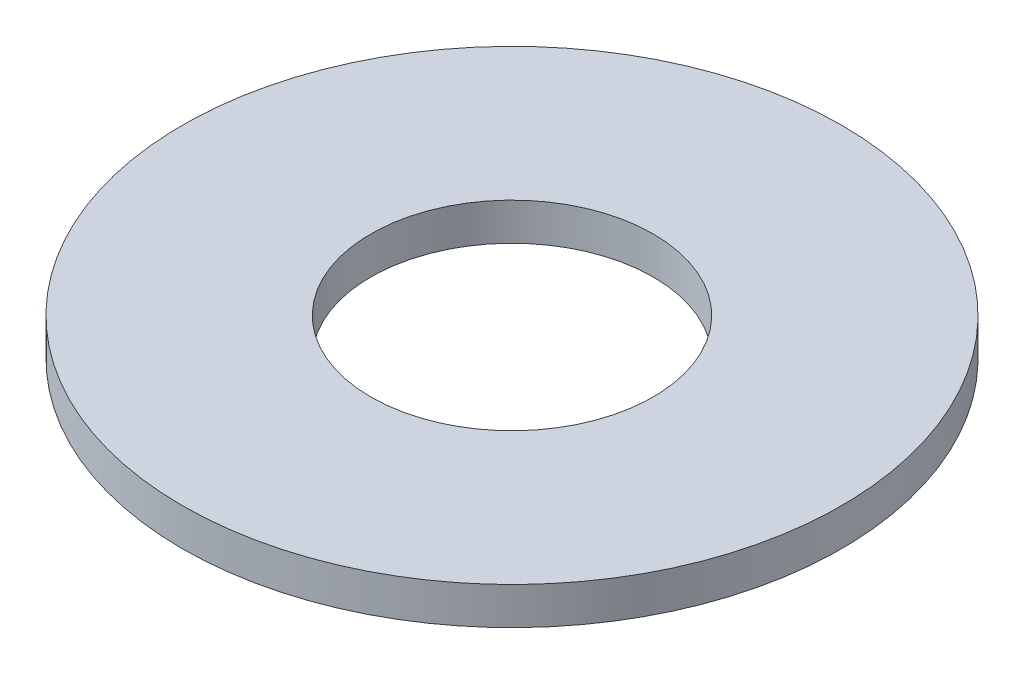
SolidWorks part; units mm, degrees
material "Silicon Rubber"
ref_plane "Front Plane" through (0, 0, 0) normal (0, 0, 1) x (1, 0, 0)
ref_plane "Top Plane" through (0, 0, 0) normal (0, 1, 0) x (1, 0, 0)
ref_plane "Right Plane" through (0, 0, 0) normal (1, 0, 0) x (0, 0, -1)
sketch "Sketch1" plane through (0, 0, 0) normal (0, 1, 0) x (1, 0, 0)
  circle A0 centre (0, 0) radius 7
  circle A1 centre (0, 0) radius 3
  dimension "D1" = 6
  dimension "D2" = 14
extrude "Boss-Extrude1" add sketch "Sketch1" along normal blind 0.7937
